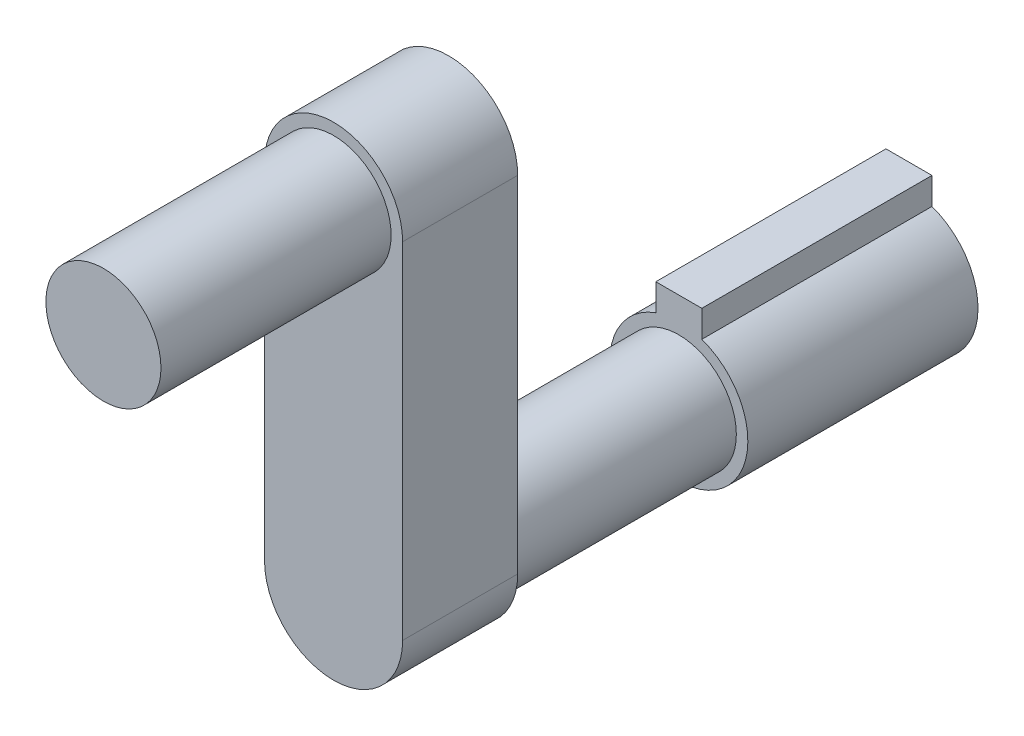
SolidWorks part; units mm, degrees
ref_plane "Front Plane" through (0, 0, 0) normal (0, 0, 1) x (1, 0, 0)
ref_plane "Top Plane" through (0, 0, 0) normal (0, 1, 0) x (1, 0, 0)
ref_plane "Right Plane" through (0, 0, 0) normal (1, 0, 0) x (0, 0, -1)
sketch "Sketch1" plane through (0, 0, 0) normal (0, 0, 1) x (1, 0, 0)
  line L1 (1, 2.0032) -> (-1, 2.0032)
  line L2 (1, 2.0032) -> (1, 3.9968)
  line L3 (1, 3.9968) -> (-1, 3.9968)
  line L4 (-1, 2.0032) -> (-1, 3.9968)
  line L5 (1, 2.0032) -> (-1, 3.9968) construction
  line L6 (1, 3.9968) -> (-1, 2.0032) construction
  circle A0 centre (0, 0) radius 3
  point P3 (0, 3)
  dimension "D2" = 6
  dimension "D1" = 2
  dimension "D3" = 4.12
extrude "Boss-Extrude1" add sketch "Sketch1" along normal blind 10 contours A0 L2 L3 L4
sketch "Sketch2" plane through (0, 0, 10) normal (0, 0, 1) x (1, 0, 0)
  circle A0 centre (0, 0) radius 2.5
  dimension "D1" = 5
extrude "Boss-Extrude2" add sketch "Sketch2" along normal blind 10
sketch "Sketch3" plane through (0, 0, 20) normal (0, 0, 1) x (1, 0, 0)
  line L0 (0, 0) -> (0, 15) construction
  line L1 (-3, 0) -> (-3, 15)
  line L2 (3, 0) -> (3, 15)
  arc A0 (-3, 0) -> (3, 0) centre (0, 0) ccw
  arc A1 (3, 15) -> (-3, 15) centre (0, 15) ccw
  point P3 (0, 7.5)
  dimension "D1" = 3
  dimension "D2" = 15
extrude "Boss-Extrude3" add sketch "Sketch3" along normal blind 5
sketch "Sketch4" plane through (0, 0, 25) normal (0, 0, 1) x (1, 0, 0)
  circle A0 centre (0, 15) radius 2.5
  dimension "D1" = 5
extrude "Boss-Extrude4" add sketch "Sketch4" along normal blind 10
sketch "Sketch5" plane through (-3, 0, 0) normal (-1, 0, 0) x (0, 0, 1)
  text T0 "APSC PASS" font "Century Gothic" height 3.5
extrude "Cut-Extrude1" cut sketch "Sketch5" against normal blind 2
